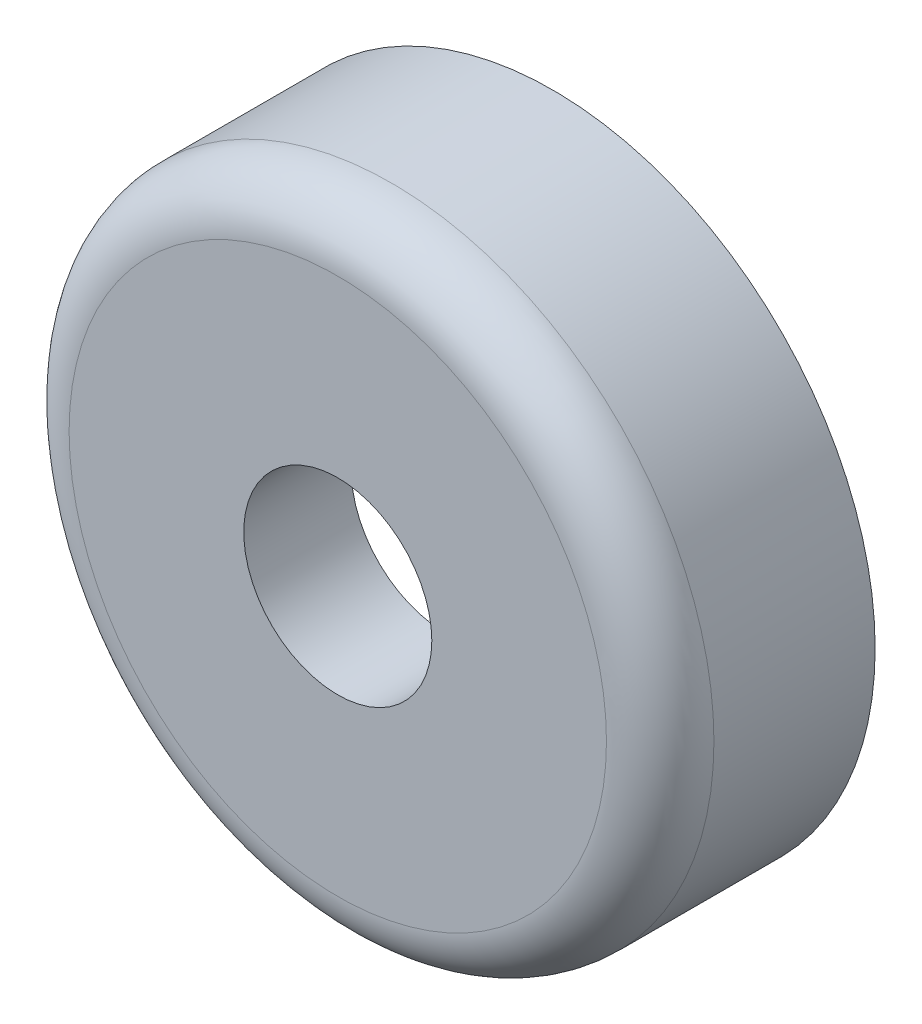
SolidWorks part; units mm, degrees
ref_plane "Front Plane" through (0, 0, 0) normal (0, 0, 1) x (1, 0, 0)
ref_plane "Top Plane" through (0, 0, 0) normal (0, 1, 0) x (1, 0, 0)
ref_plane "Right Plane" through (0, 0, 0) normal (1, 0, 0) x (0, 0, -1)
sketch "Sketch1" plane through (0, 0, 0) normal (0, 0, 1) x (1, 0, 0)
  circle A0 centre (0, 0) radius 4.1
  circle A1 centre (0, 0) radius 6
  dimension "D1" = 8.2
  dimension "12" = 12
extrude "Boss-Extrude1" add sketch "Sketch1" along normal blind 2
sketch "Sketch2" plane through (0, 0, 2) normal (0, 0, 1) x (1, 0, 0)
  circle A0 centre (0, 0) radius 6
  circle A1 centre (0, 0) radius 1.75
  dimension "D1" = 3.5
extrude "Boss-Extrude2" add sketch "Sketch2" along normal blind 2
fillet "Fillet1" radius 1 2 edges at (6, 0, 4) (4.1, 0, 0)
